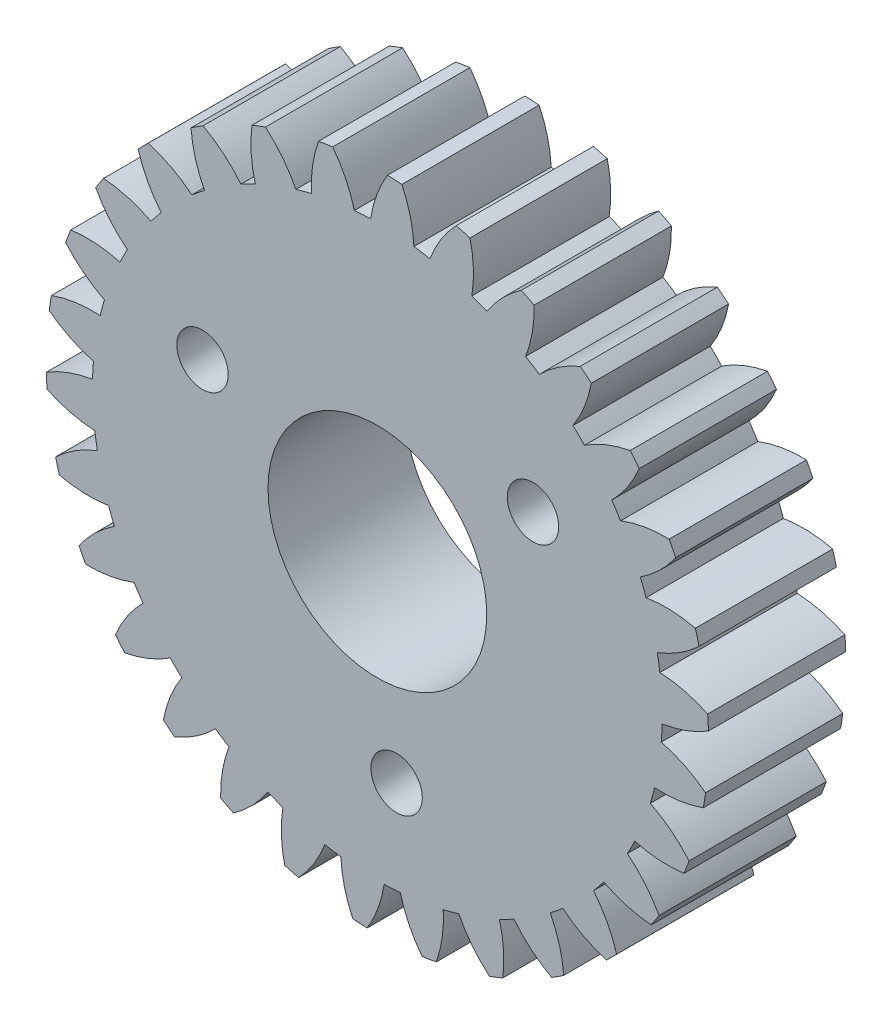
SolidWorks part; units mm, degrees
ref_plane "Front Plane" through (0, 0, 0) normal (0, 0, 1) x (1, 0, 0)
ref_plane "Top Plane" through (0, 0, 0) normal (0, 1, 0) x (1, 0, 0)
ref_plane "Right Plane" through (0, 0, 0) normal (1, 0, 0) x (0, 0, -1)
sketch "Sketch1" plane through (0, 0, 0) normal (0, 0, 1) x (1, 0, 0)
  circle A0 centre (0, 0) radius 53.6981
extrude "Boss-Extrude1" add sketch "Sketch1" along normal blind 10
extrude "Cut-Extrude1" cut sketch "Sketch2" against normal through all contours A131 A479 A478 A477 A476 A475 A474 A473 A472 A471 A470 A469 A468 A467 A466 A465 A464 A463 A462 A461 A460 A459 A458 A457 A456 A455 A454 A453 A452 A451 A450 A449 A448 A447 A446 A445 A444 A443 A442 A441 A440 A439 A438 A437 A436 A435 A434 A433 A432 A431 | A130 | A133
sketch "Sketch2" plane through (58.9639, -183.173, 105.5946) normal (0, 0, 1) x (1, 0, 0)
  circle A123 centre (-49.3823, 186.0412) radius 1.873
  circle A126 centre (-59.3167, 163.9803) radius 1.873
  circle A130 centre (-73.4549, 183.6142) radius 1.873
  circle A131 centre (-60.718, 177.8786) radius 231.8084
  circle A133 centre (-60.718, 177.8786) radius 7.9687
  arc A360 (-71.5203, 160.161) -> (-72.135, 156.6238) centre (-63.0111, 156.8602) ccw
  arc A361 (-72.135, 156.6238) -> (-71.2026, 156.1488) centre (-60.718, 177.8786) ccw
  arc A362 (-71.2026, 156.1488) -> (-68.7024, 158.7252) centre (-76.3743, 163.6691) ccw
  arc A363 (-68.7024, 158.7252) -> (-67.6005, 158.3022) centre (-60.718, 177.8786) ccw
  arc A364 (-67.6005, 158.3022) -> (-67.4664, 154.7146) centre (-58.591, 156.8427) ccw
  arc A365 (-67.4664, 154.7146) -> (-66.4556, 154.4437) centre (-60.718, 177.8786) ccw
  arc A366 (-66.4556, 154.4437) -> (-64.5457, 157.4837) centre (-73.0779, 160.7245) ccw
  arc A367 (-64.5457, 157.4837) -> (-63.38, 157.299) centre (-60.718, 177.8786) ccw
  arc A368 (-63.38, 157.299) -> (-62.5029, 153.8177) centre (-54.2639, 157.7447) ccw
  arc A369 (-62.5029, 153.8177) -> (-61.4579, 153.7629) centre (-60.718, 177.8786) ccw
  arc A370 (-61.4579, 153.7629) -> (-60.2217, 157.1335) centre (-69.2413, 158.5296) ccw
  arc A371 (-60.2217, 157.1335) -> (-59.0431, 157.1953) centre (-60.718, 177.8786) ccw
  arc A372 (-59.0431, 157.1953) -> (-57.4613, 153.9724) centre (-50.2188, 159.5265) ccw
  arc A373 (-57.4613, 153.9724) -> (-56.4278, 154.1361) centre (-60.718, 177.8786) ccw
  arc A374 (-56.4278, 154.1361) -> (-55.9194, 157.69) centre (-65.0321, 157.1803) ccw
  arc A375 (-55.9194, 157.69) -> (-54.7794, 157.9955) centre (-60.718, 177.8786) ccw
  arc A376 (-54.7794, 157.9955) -> (-52.5621, 155.1719) centre (-46.6327, 162.1104) ccw
  arc A377 (-52.5621, 155.1719) -> (-51.5852, 155.5469) centre (-60.718, 177.8786) ccw
  arc A378 (-51.5852, 155.5469) -> (-51.8268, 159.1289) centre (-60.6345, 156.7357) ccw
  arc A379 (-51.8268, 159.1289) -> (-50.7752, 159.6647) centre (-60.718, 177.8786) ccw
  arc A380 (-50.7752, 159.6647) -> (-48.0193, 157.3638) centre (-43.6621, 165.3835) ccw
  arc A381 (-48.0193, 157.3638) -> (-47.1418, 157.9337) centre (-60.718, 177.8786) ccw
  arc A382 (-47.1418, 157.9337) -> (-48.1228, 161.3872) centre (-56.2404, 157.215) ccw
  arc A383 (-48.1228, 161.3872) -> (-47.2056, 162.1299) centre (-60.718, 177.8786) ccw
  arc A384 (-47.2056, 162.1299) -> (-44.0316, 160.4523) centre (-41.4369, 169.2027) ccw
  arc A385 (-44.0316, 160.4523) -> (-43.2917, 161.1922) centre (-60.718, 177.8786) ccw
  arc A386 (-43.2917, 161.1922) -> (-44.9693, 164.3662) centre (-52.0421, 158.5975) ccw
  arc A387 (-44.9693, 164.3662) -> (-44.2266, 165.2834) centre (-60.718, 177.8786) ccw
  arc A388 (-44.2266, 165.2834) -> (-40.7731, 164.3024) centre (-40.0544, 173.401) ccw
  arc A389 (-40.7731, 164.3024) -> (-40.2032, 165.18) centre (-60.718, 177.8786) ccw
  arc A390 (-40.2032, 165.18) -> (-42.5041, 167.9358) centre (-48.2229, 160.8227) ccw
  arc A391 (-42.5041, 167.9358) -> (-41.9683, 168.9874) centre (-60.718, 177.8786) ccw
  arc A392 (-41.9683, 168.9874) -> (-38.3863, 168.7458) centre (-39.575, 177.7951) ccw
  arc A393 (-38.3863, 168.7458) -> (-38.0113, 169.7227) centre (-60.718, 177.8786) ccw
  arc A394 (-38.0113, 169.7227) -> (-40.8349, 171.94) centre (-44.9498, 163.7933) ccw
  arc A395 (-40.8349, 171.94) -> (-40.5294, 173.08) centre (-60.718, 177.8786) ccw
  arc A396 (-40.5294, 173.08) -> (-36.9755, 173.5884) centre (-40.0197, 182.1927) ccw
  arc A397 (-36.9755, 173.5884) -> (-36.8118, 174.6219) centre (-60.718, 177.8786) ccw
  arc A398 (-36.8118, 174.6219) -> (-40.0347, 176.2037) centre (-42.3659, 167.3794) ccw
  arc A399 (-40.0347, 176.2037) -> (-39.9729, 177.3823) centre (-60.718, 177.8786) ccw
  arc A400 (-39.9729, 177.3823) -> (-36.6023, 178.6185) centre (-41.369, 186.4019) ccw
  arc A401 (-36.6023, 178.6185) -> (-36.6571, 179.6635) centre (-60.718, 177.8786) ccw
  arc A402 (-36.6571, 179.6635) -> (-40.1384, 180.5406) centre (-40.584, 171.4245) ccw
  arc A403 (-40.1384, 180.5406) -> (-40.323, 181.7063) centre (-60.718, 177.8786) ccw
  arc A404 (-40.323, 181.7063) -> (-37.2831, 183.6163) centre (-43.5639, 190.2385) ccw
  arc A405 (-37.2831, 183.6163) -> (-37.554, 184.627) centre (-60.718, 177.8786) ccw
  arc A406 (-37.554, 184.627) -> (-41.1416, 184.7611) centre (-39.6821, 175.7516) ccw
  arc A407 (-41.1416, 184.7611) -> (-41.5645, 185.863) centre (-60.718, 177.8786) ccw
  arc A408 (-41.5645, 185.863) -> (-38.9882, 188.3632) centre (-46.5085, 193.5349) ccw
  arc A409 (-38.9882, 188.3632) -> (-39.4632, 189.2956) centre (-60.718, 177.8786) ccw
  arc A410 (-39.4632, 189.2956) -> (-43.0004, 188.6809) centre (-39.6996, 180.1717) ccw
  arc A411 (-43.0004, 188.6809) -> (-43.6431, 189.6707) centre (-60.718, 177.8786) ccw
  arc A412 (-43.6431, 189.6707) -> (-41.6429, 192.652) centre (-50.0742, 196.1471) ccw
  arc A413 (-41.6429, 192.652) -> (-42.3014, 193.4652) centre (-60.718, 177.8786) ccw
  arc A414 (-42.3014, 193.4652) -> (-45.6335, 192.1285) centre (-40.6357, 184.4915) ccw
  arc A415 (-45.6335, 192.1285) -> (-46.468, 192.9631) centre (-60.718, 177.8786) ccw
  arc A416 (-46.468, 192.9631) -> (-45.1313, 196.2951) centre (-54.105, 197.9609) ccw
  arc A417 (-45.1313, 196.2951) -> (-45.9445, 196.9536) centre (-60.718, 177.8786) ccw
  arc A418 (-45.9445, 196.9536) -> (-48.9258, 194.9534) centre (-42.4494, 188.5224) ccw
  arc A419 (-48.9258, 194.9534) -> (-49.9156, 195.5962) centre (-60.718, 177.8786) ccw
  arc A420 (-49.9156, 195.5962) -> (-49.3009, 199.1333) centre (-58.4249, 198.8969) ccw
  arc A421 (-49.3009, 199.1333) -> (-50.2333, 199.6084) centre (-60.718, 177.8786) ccw
  arc A422 (-50.2333, 199.6084) -> (-52.7336, 197.032) centre (-45.0616, 192.088) ccw
  arc A423 (-52.7336, 197.032) -> (-53.8354, 197.4549) centre (-60.718, 177.8786) ccw
  arc A424 (-53.8354, 197.4549) -> (-53.9695, 201.0426) centre (-62.8449, 198.9144) ccw
  arc A425 (-53.9695, 201.0426) -> (-54.9803, 201.3134) centre (-60.718, 177.8786) ccw
  arc A426 (-54.9803, 201.3134) -> (-56.8903, 198.2735) centre (-48.358, 195.0326) ccw
  arc A427 (-56.8903, 198.2735) -> (-58.0559, 198.4581) centre (-60.718, 177.8786) ccw
  arc A428 (-58.0559, 198.4581) -> (-58.9331, 201.9395) centre (-67.1721, 198.0125) ccw
  arc A429 (-58.9331, 201.9395) -> (-59.978, 201.9942) centre (-60.718, 177.8786) ccw
  arc A430 (-59.978, 201.9942) -> (-61.2143, 198.6236) centre (-52.1947, 197.2276) ccw
  arc A431 (-61.2143, 198.6236) -> (-62.3928, 198.5619) centre (-60.718, 177.8786) ccw
  arc A432 (-62.3928, 198.5619) -> (-63.9746, 201.7848) centre (-71.2171, 196.2306) ccw
  arc A433 (-63.9746, 201.7848) -> (-65.0081, 201.6211) centre (-60.718, 177.8786) ccw
  arc A434 (-65.0081, 201.6211) -> (-65.5166, 198.0671) centre (-56.4038, 198.5768) ccw
  arc A435 (-65.5166, 198.0671) -> (-66.6565, 197.7617) centre (-60.718, 177.8786) ccw
  arc A436 (-66.6565, 197.7617) -> (-68.8738, 200.5853) centre (-74.8033, 193.6467) ccw
  arc A437 (-68.8738, 200.5853) -> (-69.8507, 200.2103) centre (-60.718, 177.8786) ccw
  arc A438 (-69.8507, 200.2103) -> (-69.6091, 196.6283) centre (-60.8015, 199.0215) ccw
  arc A439 (-69.6091, 196.6283) -> (-70.6607, 196.0925) centre (-60.718, 177.8786) ccw
  arc A440 (-70.6607, 196.0925) -> (-73.4166, 198.3934) centre (-77.7739, 190.3736) ccw
  arc A441 (-73.4166, 198.3934) -> (-74.2942, 197.8235) centre (-60.718, 177.8786) ccw
  arc A442 (-74.2942, 197.8235) -> (-73.3131, 194.37) centre (-65.1955, 198.5421) ccw
  arc A443 (-73.3131, 194.37) -> (-74.2303, 193.6272) centre (-60.718, 177.8786) ccw
  arc A444 (-74.2303, 193.6272) -> (-77.4044, 195.3049) centre (-79.999, 186.5545) ccw
  arc A445 (-77.4044, 195.3049) -> (-78.1443, 194.565) centre (-60.718, 177.8786) ccw
  arc A446 (-78.1443, 194.565) -> (-76.4666, 191.3909) centre (-69.3939, 197.1596) ccw
  arc A447 (-76.4666, 191.3909) -> (-77.2094, 190.4737) centre (-60.718, 177.8786) ccw
  arc A448 (-77.2094, 190.4737) -> (-80.6629, 191.4548) centre (-81.3815, 182.3561) ccw
  arc A449 (-80.6629, 191.4548) -> (-81.2328, 190.5772) centre (-60.718, 177.8786) ccw
  arc A450 (-81.2328, 190.5772) -> (-78.9319, 187.8213) centre (-73.213, 194.9345) ccw
  arc A451 (-78.9319, 187.8213) -> (-79.4677, 186.7697) centre (-60.718, 177.8786) ccw
  arc A452 (-79.4677, 186.7697) -> (-83.0497, 187.0113) centre (-81.8609, 177.9621) ccw
  arc A453 (-83.0497, 187.0113) -> (-83.4247, 186.0344) centre (-60.718, 177.8786) ccw
  arc A454 (-83.4247, 186.0344) -> (-80.6011, 183.8172) centre (-76.4861, 191.9639) ccw
  arc A455 (-80.6011, 183.8172) -> (-80.9065, 182.6772) centre (-60.718, 177.8786) ccw
  arc A456 (-80.9065, 182.6772) -> (-84.4605, 182.1687) centre (-81.4162, 173.5644) ccw
  arc A457 (-84.4605, 182.1687) -> (-84.6242, 181.1352) centre (-60.718, 177.8786) ccw
  arc A458 (-84.6242, 181.1352) -> (-81.4013, 179.5535) centre (-79.07, 188.3777) ccw
  arc A459 (-81.4013, 179.5535) -> (-81.463, 178.3749) centre (-60.718, 177.8786) ccw
  arc A460 (-81.463, 178.3749) -> (-84.8336, 177.1386) centre (-80.067, 169.3553) ccw
  arc A461 (-84.8336, 177.1386) -> (-84.7789, 176.0937) centre (-60.718, 177.8786) ccw
  arc A462 (-84.7789, 176.0937) -> (-81.2975, 175.2166) centre (-80.8519, 184.3327) ccw
  arc A463 (-81.2975, 175.2166) -> (-81.1129, 174.0509) centre (-60.718, 177.8786) ccw
  arc A464 (-81.1129, 174.0509) -> (-84.1528, 172.1409) centre (-77.872, 165.5186) ccw
  arc A465 (-84.1528, 172.1409) -> (-83.882, 171.1301) centre (-60.718, 177.8786) ccw
  arc A466 (-83.882, 171.1301) -> (-80.2943, 170.996) centre (-81.7538, 180.0056) ccw
  arc A467 (-80.2943, 170.996) -> (-79.8714, 169.8942) centre (-60.718, 177.8786) ccw
  arc A468 (-79.8714, 169.8942) -> (-82.4478, 167.3939) centre (-74.9274, 162.2222) ccw
  arc A469 (-82.4478, 167.3939) -> (-81.9727, 166.4615) centre (-60.718, 177.8786) ccw
  arc A470 (-81.9727, 166.4615) -> (-78.4356, 167.0762) centre (-81.7363, 175.5855) ccw
  arc A471 (-78.4356, 167.0762) -> (-77.7928, 166.0864) centre (-60.718, 177.8786) ccw
  arc A472 (-77.7928, 166.0864) -> (-79.793, 163.1051) centre (-71.3618, 159.61) ccw
  arc A473 (-79.793, 163.1051) -> (-79.1345, 162.2919) centre (-60.718, 177.8786) ccw
  arc A474 (-79.1345, 162.2919) -> (-75.8025, 163.6286) centre (-80.8003, 171.2656) ccw
  arc A475 (-75.8025, 163.6286) -> (-74.9679, 162.7941) centre (-60.718, 177.8786) ccw
  arc A476 (-74.9679, 162.7941) -> (-76.3046, 159.462) centre (-67.3309, 157.7963) ccw
  arc A477 (-76.3046, 159.462) -> (-75.4914, 158.8035) centre (-60.718, 177.8786) ccw
  arc A478 (-75.4914, 158.8035) -> (-72.5101, 160.8038) centre (-78.9865, 167.2348) ccw
  arc A479 (-72.5101, 160.8038) -> (-71.5203, 160.161) centre (-60.718, 177.8786) ccw
